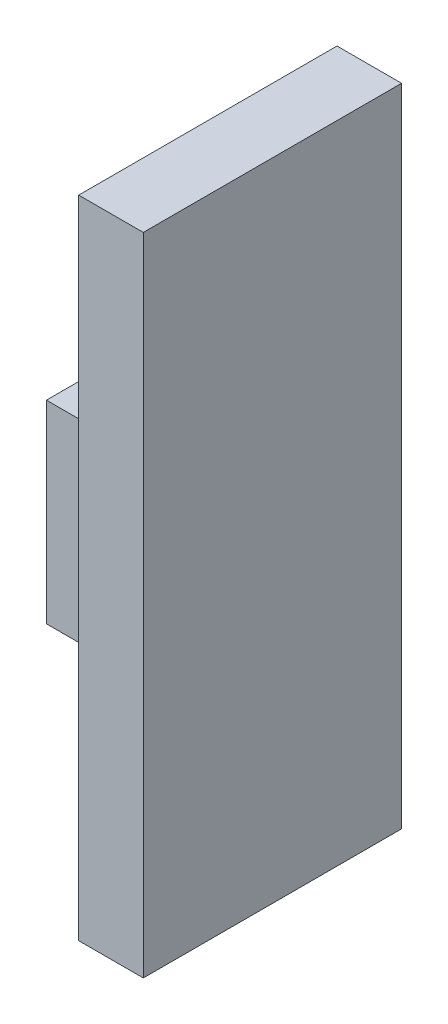
SolidWorks part; units mm, degrees
ref_plane "Front Plane" through (0, 0, 0) normal (0, 0, 1) x (1, 0, 0)
ref_plane "Top Plane" through (0, 0, 0) normal (0, 1, 0) x (1, 0, 0)
ref_plane "Right Plane" through (0, 0, 0) normal (1, 0, 0) x (0, 0, -1)
sketch "Sketch1" plane through (0, 0, 0) normal (1, 0, 0) x (0, 0, -1)
  line L0 (-20, 50) -> (20, 50)
  line L2 (-20, 50) -> (-20, -50)
  line L3 (-20, -50) -> (20, -50)
  line L4 (20, -50) -> (20, 50)
extrude "Boss-Extrude1" add sketch "Sketch1" along normal blind 10
sketch "Sketch2" plane through (0, 0, 0) normal (-1, 0, 0) x (0, 0, 1)
  line L0 (-15, 15) -> (-15, -15)
  line L3 (-15, 15) -> (15, 15)
  line L4 (15, 15) -> (15, -15)
  line L5 (15, -15) -> (-15, -15)
extrude "Boss-Extrude2" add sketch "Sketch2" along normal blind 10
sketch "Sketch3" plane through (-10, 0, 0) normal (-1, 0, 0) x (0, 0, 1)
  circle A0 centre (0, 0) radius 10
extrude "Cut-Extrude1" cut sketch "Sketch3" against normal blind 10
